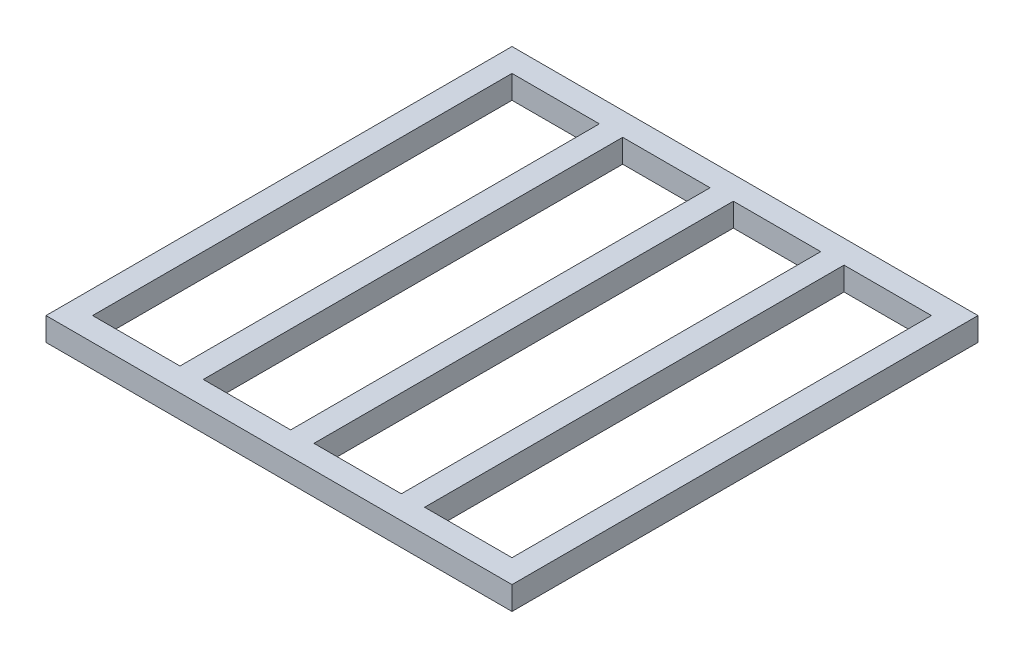
SolidWorks part; units mm, degrees
ref_plane "Front Plane" through (0, 0, 0) normal (0, 0, 1) x (1, 0, 0)
ref_plane "Top Plane" through (0, 0, 0) normal (0, 1, 0) x (1, 0, 0)
ref_plane "Right Plane" through (0, 0, 0) normal (1, 0, 0) x (0, 0, -1)
sketch "Sketch3" plane through (0, 0, 0) normal (0, 1, 0) x (1, 0, 0)
  line L0 (-28.5, 38) -> (-28.5, 2)
  line L1 (0, 0) -> (-40, 0)
  line L2 (0, 0) -> (0, 40)
  line L3 (0, 40) -> (-40, 40)
  line L4 (-40, 0) -> (-40, 40)
  line L5 (-38, 38) -> (-30.5, 38)
  line L6 (-38, 38) -> (-38, 2)
  line L7 (-38, 2) -> (-30.5, 2)
  line L8 (-30.5, 38) -> (-30.5, 2)
  line L9 (-28.5, 38) -> (-21, 38)
  line L10 (-21, 38) -> (-21, 2)
  line L11 (-28.5, 2) -> (-21, 2)
  line L12 (-19, 38) -> (-19, 2)
  line L13 (-19, 38) -> (-11.5, 38)
  line L14 (-11.5, 38) -> (-11.5, 2)
  line L15 (-19, 2) -> (-11.5, 2)
  line L16 (-9.5, 38) -> (-9.5, 2)
  line L17 (-9.5, 38) -> (-2, 38)
  line L18 (-2, 38) -> (-2, 2)
  line L19 (-9.5, 2) -> (-2, 2)
  dimension "D1" = 40
  dimension "D2" = 40
  dimension "D3" = 2
  dimension "D4" = 2
  dimension "D5" = 2
  dimension "D6" = 7.5
  dimension "D7" = 4
  dimension "D8" = 2
extrude "Boss-Extrude2" add sketch "Sketch3" along normal blind 2
